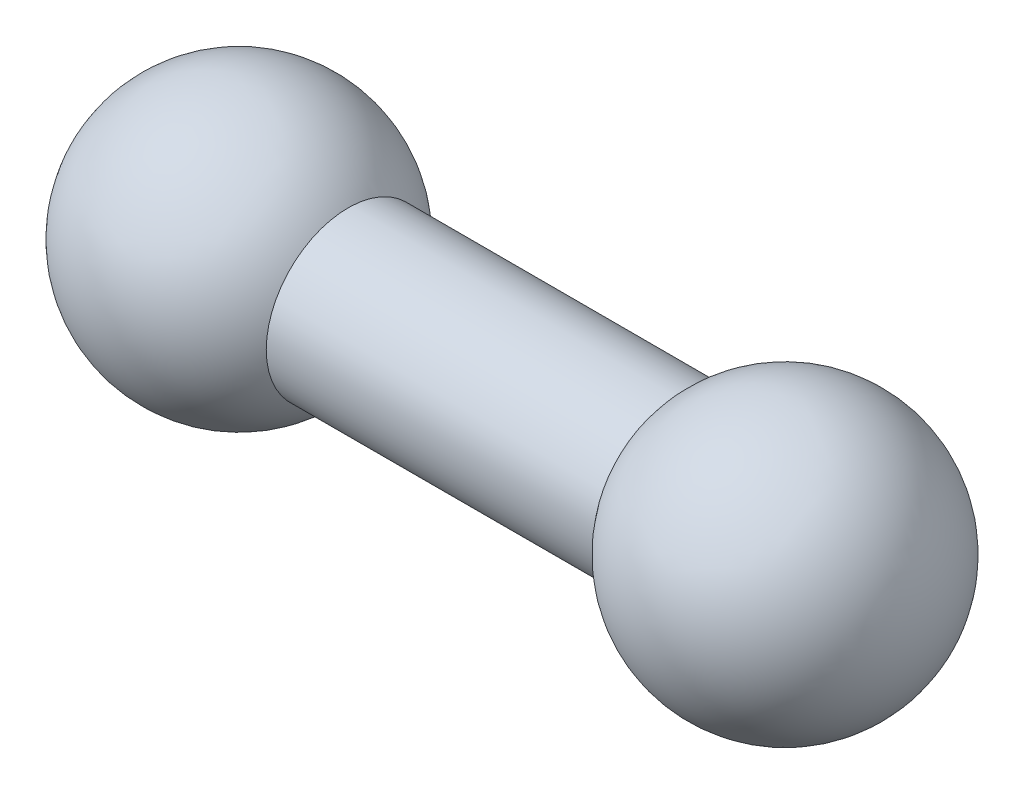
SolidWorks part; units mm, degrees
ref_plane "Front Plane" through (0, 0, 0) normal (0, 0, 1) x (1, 0, 0)
ref_plane "Top Plane" through (0, 0, 0) normal (0, 1, 0) x (1, 0, 0)
ref_plane "Right Plane" through (0, 0, 0) normal (1, 0, 0) x (0, 0, -1)
sketch "Sketch4" plane through (0, 0, 0) normal (1, 0, 0) x (0, 0, -1)
  line L0 (0, 0) -> (2.5, 0)
  line L1 (2.5, 0) -> (2.5, -2.5)
  arc A0 (0, 0) -> (2.5, -2.5) centre (2.5, 0) ccw
  dimension "D3" = 2.5
  dimension "D1" = 2.5
  dimension "D2" = 2.5
revolve "Semi-circle Revolve" add sketch "Sketch4" angle 360 about L1
mirror "Full-circle Mirror" about plane through (0, 0, 0) normal (0, -1, 0) of "Semi-circle Revolve"
sketch "Sketch5" plane through (0, 0, 0) normal (1, 0, 0) x (0, 0, -1)
  line L0 (0, 0) -> (2.5, 0) construction
  circle A0 centre (2.5, 0) radius 1.5
  dimension "D2" = 3
  dimension "D1" = 2.5
extrude "Shaft" add sketch "Sketch5" along normal blind 10
sketch "Sketch6" plane through (10, 0, 0) normal (1, 0, 0) x (0, 0, -1)
  line L0 (0, 0) -> (2.5, 0)
  line L1 (2.5, 0) -> (2.5, -2.5)
  arc A0 (0, 0) -> (2.5, -2.5) centre (2.5, 0) ccw
  dimension "D1" = 2.5
  dimension "D2" = 2.5
revolve "Opposite Semi-circle Revolve" add sketch "Sketch6" angle 360 about L1
mirror "Opposite Full-circle Mirror" about plane through (10, 0, 0) normal (0, 1, 0) of "Opposite Semi-circle Revolve"
